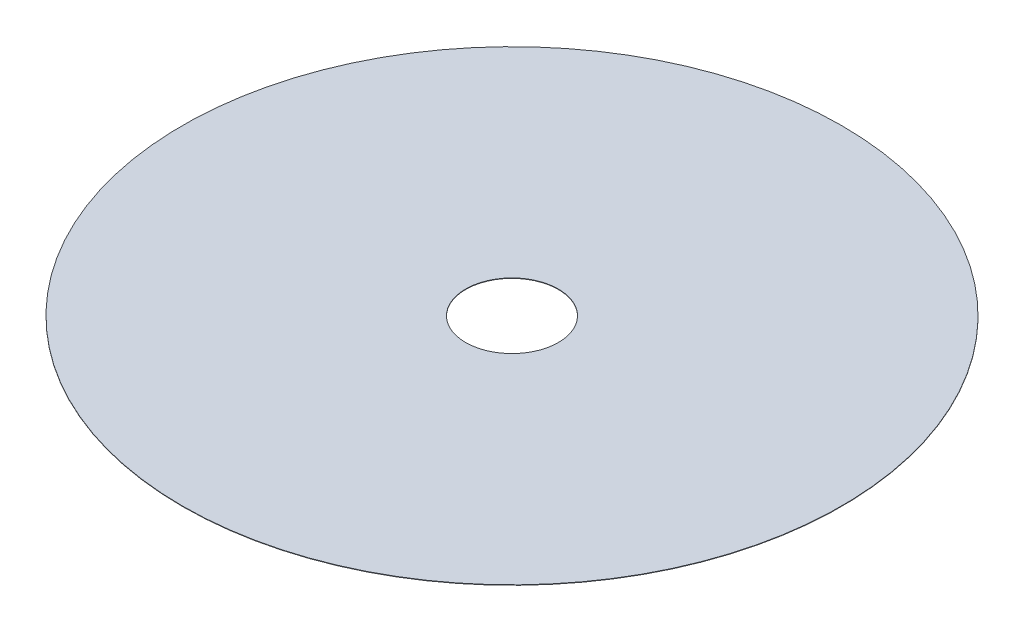
SolidWorks part; units mm, degrees
material "Custom Plastic"
ref_plane "Front Plane" through (0, 0, 0) normal (0, 0, 1) x (1, 0, 0)
ref_plane "Top Plane" through (0, 0, 0) normal (0, 1, 0) x (1, 0, 0)
ref_plane "Right Plane" through (0, 0, 0) normal (1, 0, 0) x (0, 0, -1)
sketch "Sketch1" plane through (0, 0, 0) normal (0, 1, 0) x (1, 0, 0)
  circle A0 centre (0, 0) radius 27.5
  circle A1 centre (0, 0) radius 195.5
  dimension "D1" = 55
  dimension "D2" = 391
extrude "Boss-Extrude1" add sketch "Sketch1" along normal blind 0.25
